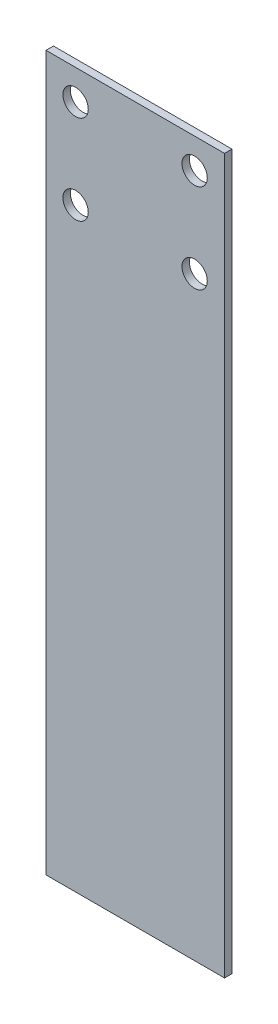
SolidWorks part; units mm, degrees
ref_plane "Front Plane" through (0, 0, 0) normal (0, 0, 1) x (1, 0, 0)
ref_plane "Top Plane" through (0, 0, 0) normal (0, 1, 0) x (1, 0, 0)
ref_plane "Right Plane" through (0, 0, 0) normal (1, 0, 0) x (0, 0, -1)
sketch "Sketch1" plane through (0, 0, 0) normal (0, 0, 1) x (1, 0, 0)
  line L1 (-74.4141, 73.5211) -> (1.7859, 73.5211)
  line L2 (-74.4141, 73.5211) -> (-74.4141, -231.2789)
  line L3 (-74.4141, -231.2789) -> (1.7859, -231.2789)
  line L4 (1.7859, 73.5211) -> (1.7859, -231.2789)
  dimension "D1" = 76.2
  dimension "D2" = 304.8
extrude "Boss-Extrude1" add sketch "Sketch1" along normal blind 3.175
sketch "Sketch2" plane through (0, 0, 3.175) normal (0, 0, 1) x (1, 0, 0)
  line L0 (-74.4141, 61.7264) -> (1.7859, 61.7264) construction
  line L1 (-74.4141, 73.5211) -> (-74.4141, -231.2789) construction
  line L2 (1.7859, -231.2789) -> (1.7859, 73.5211) construction
  line L3 (-74.4141, 73.5211) -> (-74.4141, 60.7417)
  line L4 (-74.4141, 60.7417) -> (-61.7904, 60.7417)
  circle A0 centre (-61.7904, 60.7417) radius 5.4063
  circle A1 centre (-10.9904, 60.7417) radius 5.4063
  circle A2 centre (-61.7904, 22.6417) radius 5.4063
  circle A3 centre (-10.9904, 22.6417) radius 5.4063
  dimension "D1" = 2
  dimension "D2" = 2
extrude "Cut-Extrude3" cut sketch "Sketch2" against normal blind 3.175
